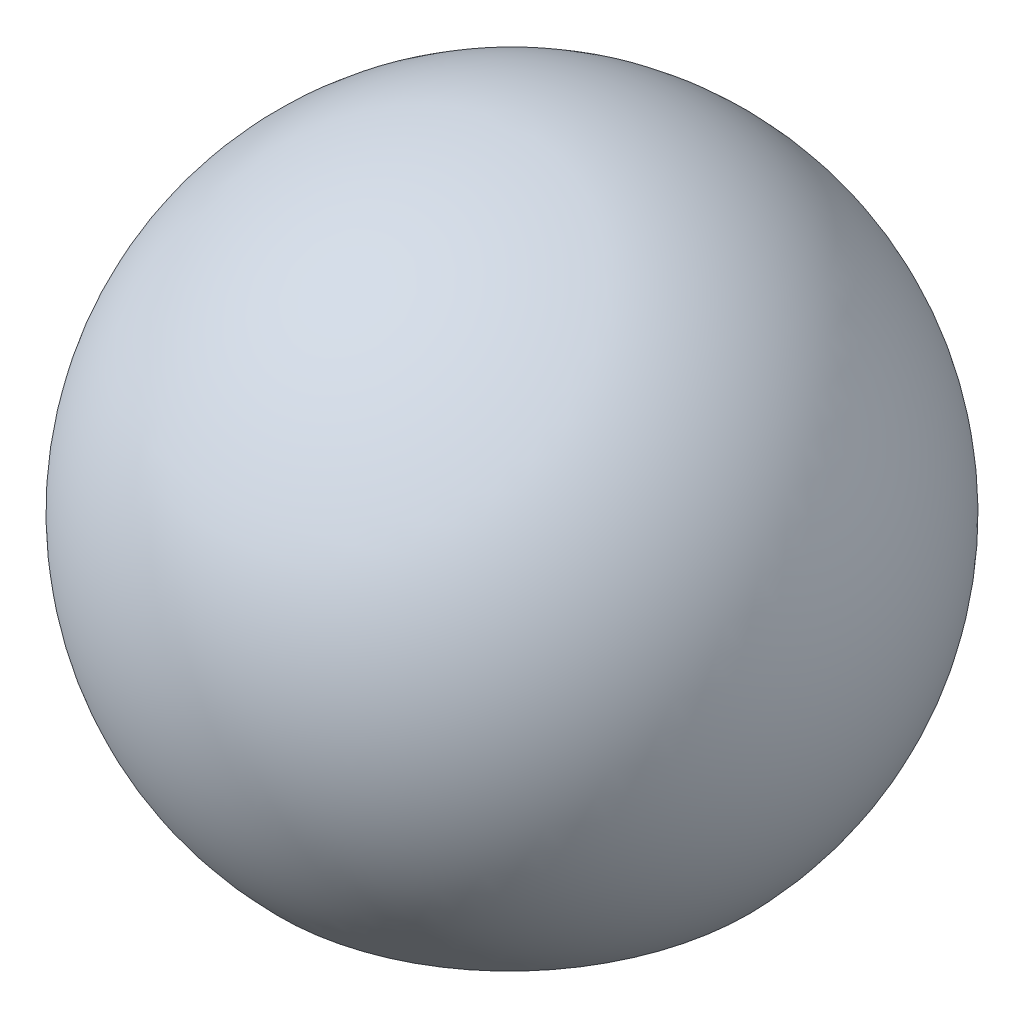
SolidWorks part; units mm, degrees
material "Natural Rubber"
ref_plane "Front Plane" through (0, 0, 0) normal (0, 0, 1) x (1, 0, 0)
ref_plane "Top Plane" through (0, 0, 0) normal (0, 1, 0) x (1, 0, 0)
ref_plane "Right Plane" through (0, 0, 0) normal (1, 0, 0) x (0, 0, -1)
sketch "Sketch2" plane through (0, 0, 0) normal (0, 0, 1) x (1, 0, 0)
  line L0 (0, 0) -> (-3.6109, 150)
  line L1 (0, 0) -> (2.6268, -109.1206)
  line L2 (2.6268, -109.1206) -> (-102.9841, -109.1206)
  arc A0 (-3.6109, 150) -> (-102.9841, -109.1206) centre (0, 0) ccw
  dimension "D1" = 150
revolve "Revolve3" add sketch "Sketch2" angle 360 about L0
